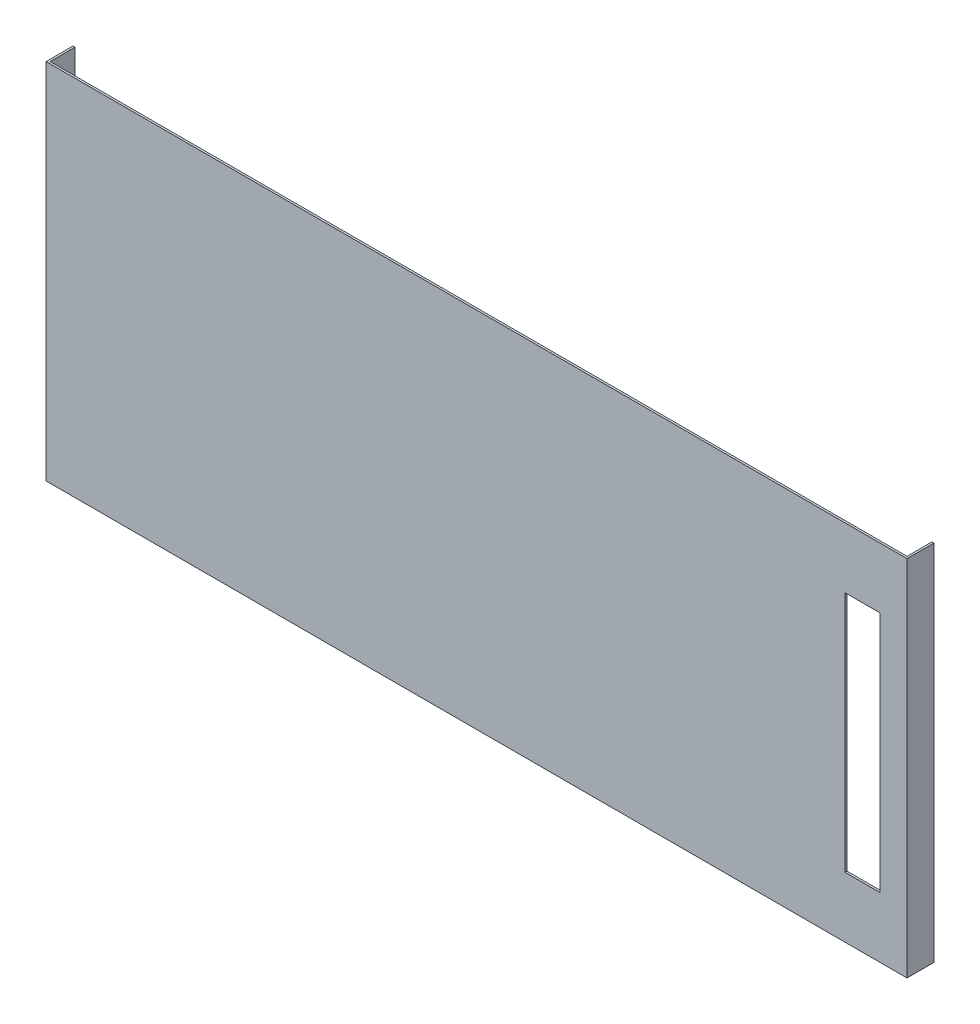
SolidWorks part; units mm, degrees
ref_plane "Front Plane" through (0, 0, 0) normal (0, 0, 1) x (1, 0, 0)
ref_plane "Top Plane" through (0, 0, 0) normal (0, 1, 0) x (1, 0, 0)
ref_plane "Right Plane" through (0, 0, 0) normal (1, 0, 0) x (0, 0, -1)
other "Configuration Table"
sketch "Sketch1" plane through (0, 0, 0) normal (0, 1, 0) x (1, 0, 0)
  line L0 (30, -40) -> (30, -20)
  line L1 (30, -20) -> (31.5, -20)
  line L2 (31.5, -20) -> (31.5, -38.5)
  line L3 (31.5, -38.5) -> (668.5, -38.5)
  line L4 (668.5, -38.5) -> (668.5, -20)
  line L5 (668.5, -20) -> (670, -20)
  line L6 (670, -20) -> (670, -40)
  line L7 (670, -40) -> (30, -40)
extrude "OVEN_fan_filtre_kapagi_kapak_1" add sketch "Sketch1" along normal blind 270 from offset 1680 separate body
sketch "Sketch2" plane through (0, 0, 0) normal (0, 0, 1) x (1, 0, 0)
  line L1 (624, 1725) -> (650, 1725)
  line L2 (624, 1725) -> (624, 1905)
  line L3 (624, 1905) -> (650, 1905)
  line L4 (650, 1725) -> (650, 1905)
extrude "OVEN_fan_filtre_kapagi_kapak_2" cut sketch "Sketch2" along normal blind 14 from offset 27
